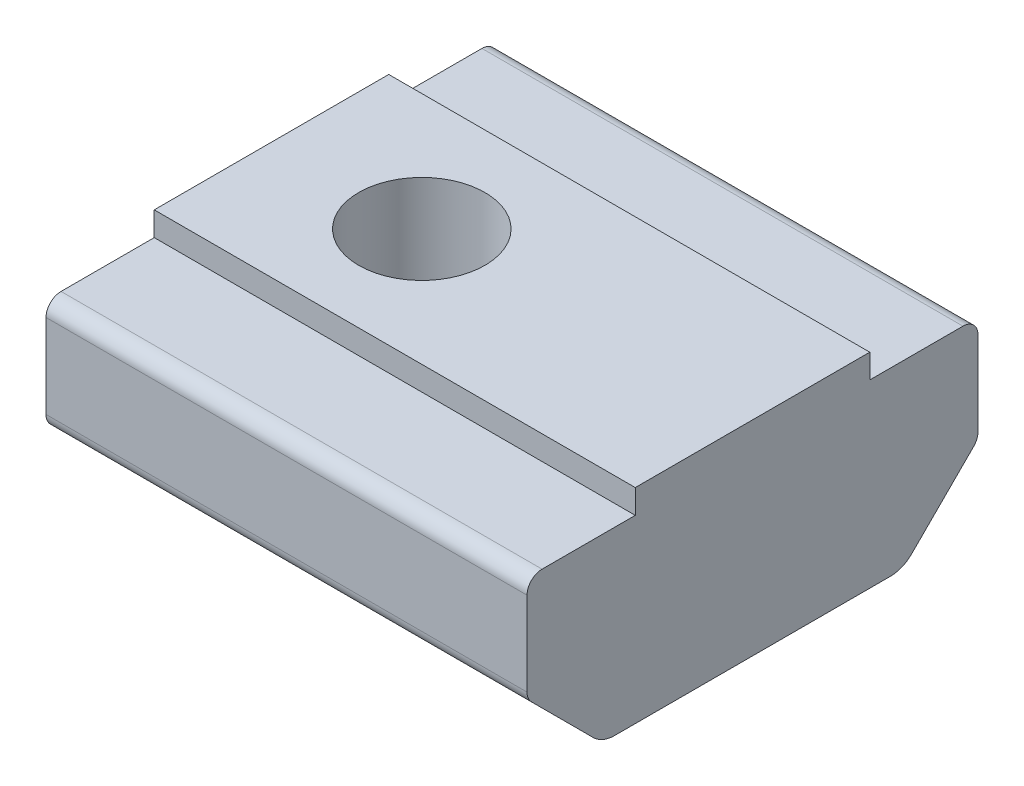
SolidWorks part; units mm, degrees
ref_plane "Front Plane" through (0, 0, 0) normal (0, 0, 1) x (1, 0, 0)
ref_plane "Top Plane" through (0, 0, 0) normal (0, 1, 0) x (1, 0, 0)
ref_plane "Right Plane" through (0, 0, 0) normal (1, 0, 0) x (0, 0, -1)
ref_plane "Plane1" through (-5, 0, 0) normal (1, 0, 0) x (0, 0, -1)
ref_plane "Plane2" through (7, 0, 0) normal (1, 0, 0) x (0, 0, -1)
sketch "Sketch1" plane through (-5, 0, 0) normal (1, 0, 0) x (0, 0, -1)
  line L0 (3.9, 0) -> (-3.9, 0)
  line L1 (-3.9, 0) -> (-3.9, -0.8)
  line L2 (-3.9, -0.8) -> (-7.5, -0.8)
  line L3 (-7.5, -0.8) -> (-7.5, -4.3)
  line L4 (-7.5, -4.3) -> (-5, -6.8)
  line L5 (-5, -6.8) -> (5, -6.8)
  line L6 (5, -6.8) -> (7.5, -4.3)
  line L7 (7.5, -4.3) -> (7.5, -0.8)
  line L8 (7.5, -0.8) -> (3.9, -0.8)
  line L9 (3.9, -0.8) -> (3.9, 0)
  line L10 (0, 0) -> (0, -6.8) construction
  point P15 (-7.5, -4.3)
  point P18 (-5, -6.8)
  point P24 (7.5, -4.3)
  dimension "FIX_8" = 10
  dimension "FIX_3" = 15
  dimension "FIX_6" = 7.8
  dimension "FIX_4" = 6.8
  dimension "FIX_5" = 6
  dimension "FIX_7" = 3.5
extrude "Boss-Extrude1" add sketch "Sketch1" along normal blind 16
fillet "Fillet1" radius 1 2 edges at (3, -6.8, 5) (3, -6.8, -5)
fillet "Fillet2" radius 0.5 4 edges at (3, -4.3, -7.5) (3, -0.8, -7.5) (3, -0.8, 7.5) (3, -4.3, 7.5)
sketch "Sketch2" plane through (7, 0, 0) normal (1, 0, 0) x (0, 0, -1)
  line L0 (0, 1.6655) -> (0, -9.505) construction
  line L2 (0, -6.6) -> (2.35, -6.6)
  line L3 (0, -6.6) -> (0, -6.8)
  line L4 (0, -6.8) -> (2.35, -6.8)
  line L5 (2.35, -6.6) -> (2.35, -6.8)
  dimension "FIX_14" = 0.2
  dimension "FIX_13" = 2.35
  dimension "FIX_12" = 6.8
revolve "Cut-Revolve1" cut sketch "Sketch2" angle 360 about L0
sketch "Sketch3" plane through (7, 0, 0) normal (1, 0, 0) x (0, 0, -1)
  line L0 (0, 0) -> (0, -7.8) construction
  line L1 (1.99, -6.6) -> (0, -6.6) construction
  line L2 (1.99, -7.8) -> (0, -7.8) construction
  line L3 (1.99, -6.6) -> (0, -6.6)
  line L4 (0, -6.6) -> (0, -7.8)
  arc A0 (0, -7.8) -> (1.99, -6.6) centre (0, -5.55) ccw
  dimension "FIX_18" = 4.5
  dimension "FIX_16" = 7.8
  dimension "FIX_17" = 6.6
revolve "Revolve1" add sketch "Sketch3" angle 360 about L0
hole_wizard "Tapped Hole1" positions "Sketch5" profile "Sketch4" tap size "M5x0.8" standard "JIS" end condition through all
sketch "Sketch5" plane through (0, 0, 0) normal (0, 1, 0) x (1, 0, 0)
  point P0 (0, 0)
cosmetic thread "Thread1" parameters "NFIX_1"=5
sketch "Sketch4" plane through (0, 0, 0) normal (1, 0, 0) x (0, 0, 1)
  line L0 (0, 0) -> (0, 7.8)
  line L1 (0, 7.8) -> (2.1, 7.8)
  line L2 (2.1, 7.8) -> (2.1, 0)
  line L5 (2.1, 0) -> (0, 0)
  line L11 (0, 0) -> (0, 7.8) construction
  dimension "Thru Tap Drill Dia." = 4.2
  dimension "Thru Tap Drill Depth" = 7.8
